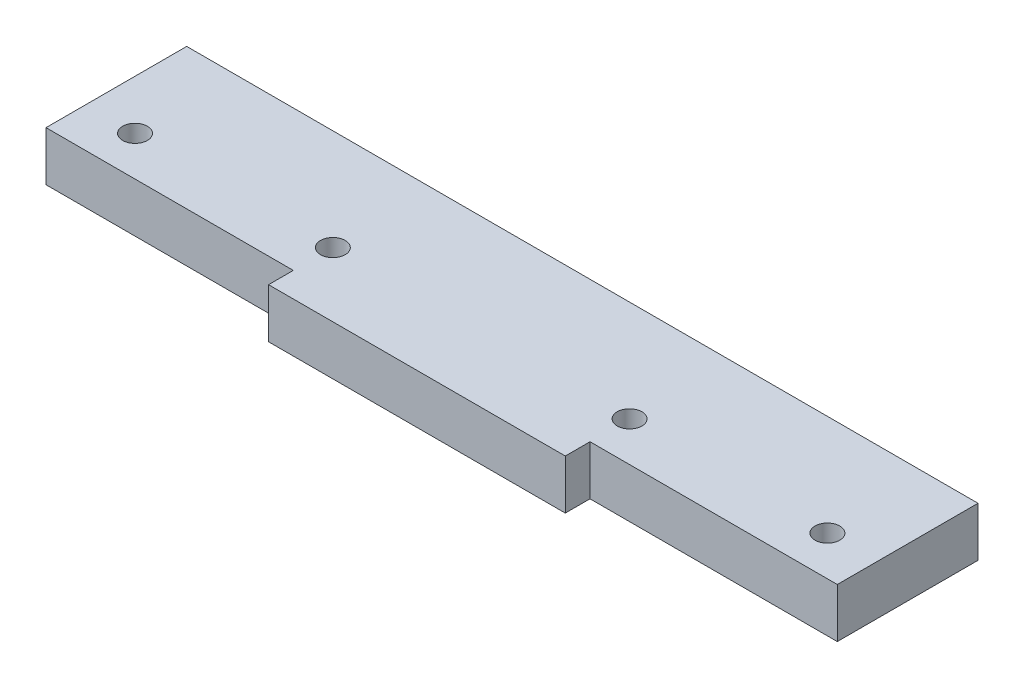
SolidWorks part; units mm, degrees
ref_plane "Front Plane" through (0, 0, 0) normal (0, 0, 1) x (1, 0, 0)
ref_plane "Top Plane" through (0, 0, 0) normal (0, 1, 0) x (1, 0, 0)
ref_plane "Right Plane" through (0, 0, 0) normal (1, 0, 0) x (0, 0, -1)
sketch "Sketch2" plane through (0, 0, 0) normal (0, 1, 0) x (1, 0, 0)
  line L1 (-80, -14.225) -> (80, -14.225)
  line L2 (-80, -14.225) -> (-80, 14.225)
  line L3 (-80, 14.225) -> (80, 14.225)
  line L4 (80, -14.225) -> (80, 14.225)
  line L5 (-80, -14.225) -> (80, 14.225) construction
  line L6 (-80, 14.225) -> (80, -14.225) construction
  point P0 (0, 0)
  dimension "D1" = 28.45
  dimension "D2" = 160
extrude "Boss-Extrude1" add sketch "Sketch2" along normal blind 10
sketch "Sketch4" plane through (0, 0, 14.225) normal (0, 0, 1) x (1, 0, 0)
  line L0 (0, 10) -> (0, 0) construction
  line L1 (-80, 10) -> (80, 10) construction
  line L2 (-80, 0) -> (80, 0) construction
  line L4 (-30, 10) -> (30, 10)
  line L5 (-30, 10) -> (-30, 0)
  line L6 (-30, 0) -> (30, 0)
  line L7 (30, 10) -> (30, 0)
  point P10 (0, 10)
  dimension "D1" = 60
extrude "Boss-Extrude2" add sketch "Sketch4" along normal blind 5
sketch "Sketch5" plane through (0, 10, 0) normal (0, 1, 0) x (1, 0, 0)
  line L0 (80, -6.225) -> (-80, -6.225) construction
  line L1 (80, -14.225) -> (80, 14.225) construction
  line L2 (-80, 14.225) -> (-80, -14.225) construction
  line L3 (0, -19.225) -> (0, 14.225) construction
  line L4 (30, -19.225) -> (-30, -19.225) construction
  line L5 (80, 14.225) -> (-80, 14.225) construction
  line L6 (30, -14.225) -> (80, -14.225) construction
  circle A0 centre (70, -6.225) radius 2.5
  circle A1 centre (30, -6.225) radius 2.5
  circle A2 centre (-30, -6.225) radius 2.5
  circle A3 centre (-70, -6.225) radius 2.5
  dimension "D1" = 5
  dimension "D2" = 40
  dimension "D3" = 10
  dimension "D4" = 8
extrude "Cut-Extrude1" cut sketch "Sketch5" against normal through all
